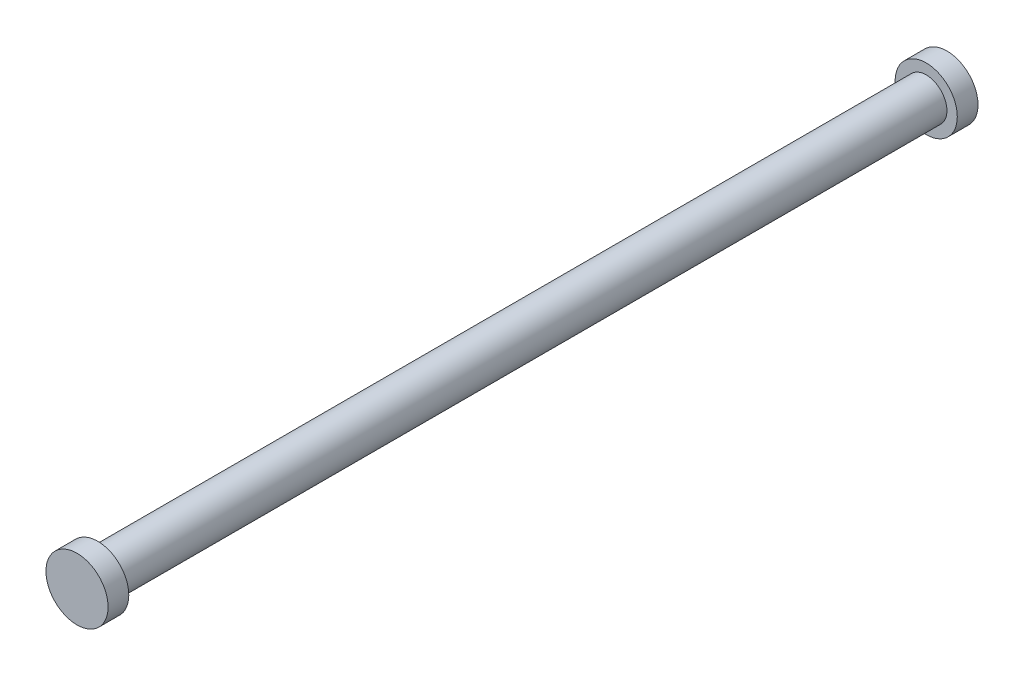
SolidWorks part; units mm, degrees
ref_plane "Plan de face" through (0, 0, 0) normal (0, 0, 1) x (1, 0, 0)
ref_plane "Plan de dessus" through (0, 0, 0) normal (0, 1, 0) x (1, 0, 0)
ref_plane "Plan de droite" through (0, 0, 0) normal (1, 0, 0) x (0, 0, -1)
sketch "Esquisse1" plane through (0, 0, 0) normal (0, 0, 1) x (1, 0, 0)
  circle A0 centre (0, 0) radius 1
  dimension "D1" = 2
extrude "Boss.-Extru.1" add sketch "Esquisse1" along normal blind 40
sketch "Esquisse2" plane through (0, 0, 40) normal (0, 0, 1) x (1, 0, 0)
  circle A0 centre (0, 0) radius 1.5
  dimension "D1" = 3
extrude "Boss.-Extru.2" add sketch "Esquisse2" along normal blind 1
ref_plane "Plan1" through (0, 0, 20) normal (0, 0, -1) x (-1, 0, 0)
mirror "Symétrie1" about plane through (0, 0, 20) normal (0, 0, -1) of "Boss.-Extru.2"
